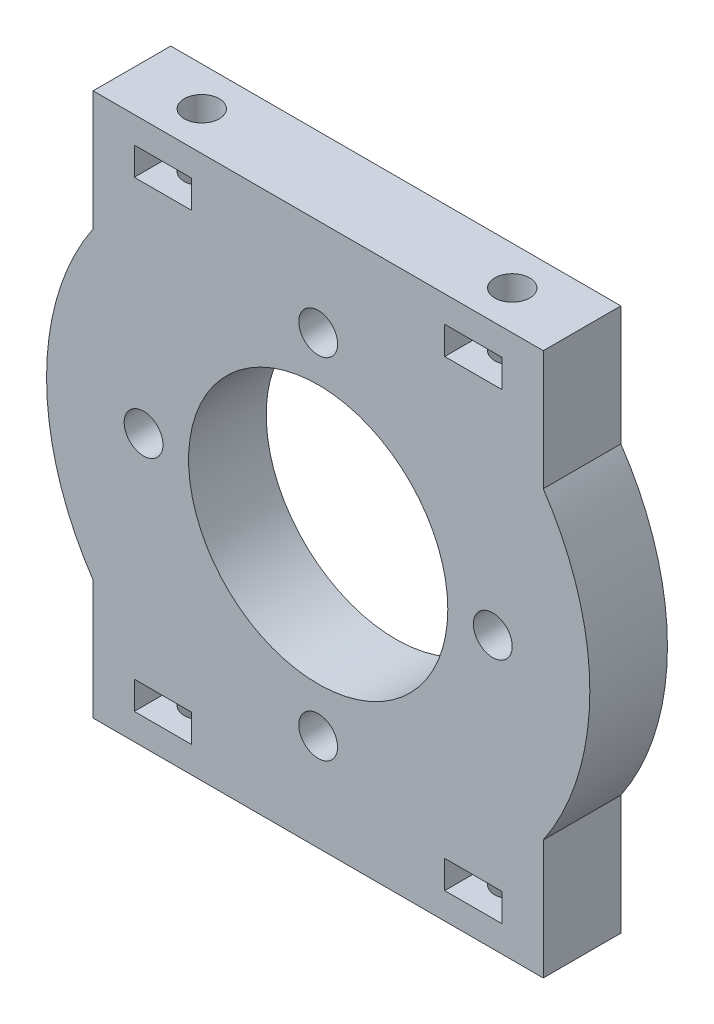
SolidWorks part; units mm, degrees
material "ABS"
ref_plane "Alzado" through (0, 0, 0) normal (0, 0, 1) x (1, 0, 0)
ref_plane "Planta" through (0, 0, 0) normal (0, 1, 0) x (1, 0, 0)
ref_plane "Vista lateral" through (0, 0, 0) normal (1, 0, 0) x (0, 0, -1)
sketch "Croquis1" plane through (0, 0, 0) normal (0, 0, 1) x (1, 0, 0)
  line L0 (-29, 19.5959) -> (-29, 35)
  line L1 (-29, -35) -> (29, -35)
  line L2 (-29, -35) -> (-29, -19.5959)
  line L3 (-29, 35) -> (29, 35)
  line L4 (29, -35) -> (29, -19.5959)
  line L5 (-29, -35) -> (29, 35) construction
  line L6 (-29, 35) -> (29, -35) construction
  line L7 (29, 19.5959) -> (29, 35)
  arc A0 (-29, 19.5959) -> (-29, -19.5959) centre (0, 0) ccw
  arc A1 (29, -19.5959) -> (29, 19.5959) centre (0, 0) ccw
  circle A2 centre (0, 0) radius 16.7005
  dimension "D1" = 70
  dimension "D4" = 33.401
  dimension "D2" = 58
  dimension "D3" = 70
extrude "Saliente-Extruir1" add sketch "Croquis1" along normal mid plane 10
ref_plane "Plano1" through (0, 28, 0) normal (0, 1, 0) x (1, 0, 0)
sketch "Croquis5" plane through (0, 28, 0) normal (0, 1, 0) x (1, 0, 0)
  line L0 (20, 0) -> (-20, 0) construction
  line L1 (-23.7, -2.1362) -> (-23.7, -5)
  line L2 (-23.7, 2.1362) -> (-23.7, -2.1362)
  line L3 (-23.7, -2.1362) -> (-20, -4.2724) construction
  line L4 (-20, -4.2724) -> (-16.3, -2.1362) construction
  line L5 (-16.3, -2.1362) -> (-16.3, 2.1362)
  line L6 (-16.3, 2.1362) -> (-20, 4.2724)
  line L7 (-20, 4.2724) -> (-23.7, 2.1362)
  line L8 (16.3, 2.1362) -> (16.3, -2.1362)
  line L9 (16.3, -2.1362) -> (20, -4.2724) construction
  line L10 (20, -4.2724) -> (23.7, -2.1362) construction
  line L11 (23.7, -2.1362) -> (23.7, 2.1362)
  line L12 (23.7, 2.1362) -> (20, 4.2724)
  line L13 (20, 4.2724) -> (16.3, 2.1362)
  line L14 (29, -5) -> (-29, -5) construction
  line L15 (-23.7, -5) -> (-16.3, -5)
  line L16 (-16.3, -5) -> (-16.3, -2.1362)
  line L17 (16.3, -2.1362) -> (16.3, -5)
  line L18 (16.3, -5) -> (23.7, -5)
  line L19 (23.7, -5) -> (23.7, -2.1362)
  circle A0 centre (-20, 0) radius 3.7 construction
  circle A1 centre (20, 0) radius 3.7 construction
  point P4 (0, 0)
  dimension "D1" = 7.4
  dimension "D2" = 40
extrude "Cortar-Extruir1" cut sketch "Croquis5" along normal blind 3.6
sketch "Croquis6" plane through (0, 35, 0) normal (0, 1, 0) x (1, 0, 0)
  line L0 (0, 0) -> (-16.3, 0) construction
  line L1 (-16.3, -5) -> (-16.3, 2.1362) construction
  line L2 (-16.3, 0) -> (-23.7, 0) construction
  line L3 (-23.7, 2.1362) -> (-23.7, -5) construction
  line L4 (0, -5.5) -> (0, 5.5) construction
  circle A0 centre (-20, 0) radius 2.25
  circle A1 centre (20, 0) radius 2.25
  dimension "D1" = 4.5
extrude "Cortar-Extruir2" cut sketch "Croquis6" against normal blind 10
mirror "Simetría1" about plane through (0, 0, 0) normal (0, 1, 0) of "Cortar-Extruir2", "Cortar-Extruir1"
sketch "Croquis7" plane through (0, 0, 5) normal (0, 0, 1) x (1, 0, 0)
  circle A0 centre (0, 0) radius 22.5 construction
  circle A1 centre (0, 22.5) radius 2.5
  circle A2 centre (22.5, 0) radius 2.5
  circle A3 centre (0, -22.5) radius 2.5
  circle A4 centre (-22.5, 0) radius 2.5
  dimension "D1" = 5
  dimension "D2" = 45
  dimension "D3" = 4
extrude "Cortar-Extruir3" cut sketch "Croquis7" against normal up to next
